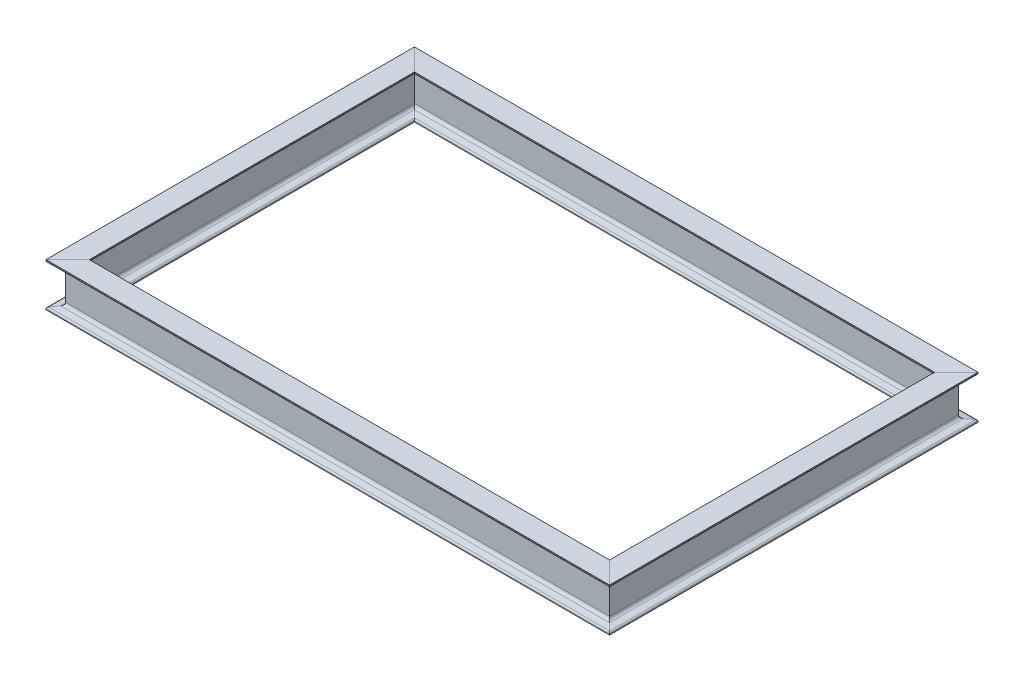
SolidWorks part; units mm, degrees
other "SB BEAM 100 x 8 x 1250 (B)"
other "SB BEAM 100 x 8 x 800 (B)"
other "SB BEAM 100 x 8 x 1250 (A)"
other "SB BEAM 100 x 8 x 800 (A)"
ref_plane "Front" through (0, 0, 0) normal (0, 0, 1) x (1, 0, 0)
ref_plane "Top" through (0, 0, 0) normal (0, 1, 0) x (1, 0, 0)
ref_plane "Right" through (0, 0, 0) normal (1, 0, 0) x (0, 0, -1)
sketch "Sketch1" plane through (0, 0, 0) normal (0, 1, 0) x (1, 0, 0)
  line L1 (-625, 400) -> (625, 400)
  line L2 (-625, 400) -> (-625, -400)
  line L3 (-625, -400) -> (625, -400)
  line L4 (625, 400) -> (625, -400)
  point P4 (0, 400)
  point P6 (-625, 0)
  dimension "D1" = 800
  dimension "D2" = 1250
other "Sb beam 100 X 8(1)"
ref_plane "Plane1" through (-625, 0, -400) normal (0, 0, 1) x (1, 0, 0)
sketch "Sketch11" plane through (-625, 0, -400) normal (0, 0, 1) x (1, 0, 0)
  line L0 (-25, -50) -> (-25, -48.0607)
  line L1 (-22.0754, -44.6083) -> (-8.0991, -42.2787)
  line L2 (-2.25, -35.374) -> (-2.25, 35.374)
  line L3 (-8.0991, 42.2787) -> (-22.0754, 44.6083)
  line L4 (-25, 48.0607) -> (-25, 50)
  line L5 (-25, 50) -> (25, 50)
  line L6 (25, 50) -> (25, 48.0607)
  line L7 (22.0754, 44.6083) -> (8.0991, 42.2787)
  line L8 (2.25, 35.374) -> (2.25, -35.374)
  line L9 (8.0991, -42.2787) -> (22.0754, -44.6083)
  line L10 (25, -48.0607) -> (25, -50)
  line L11 (25, -50) -> (-25, -50)
  line L15 (-2.25, 0) -> (2.25, 0) construction
  arc A0 (-8.0991, -42.2787) -> (-2.25, -35.374) centre (-9.25, -35.374) ccw
  arc A1 (-2.25, 35.374) -> (-8.0991, 42.2787) centre (-9.25, 35.374) ccw
  arc A2 (8.0991, 42.2787) -> (2.25, 35.374) centre (9.25, 35.374) ccw
  arc A3 (2.25, -35.374) -> (8.0991, -42.2787) centre (9.25, -35.374) ccw
  arc A4 (-22.0754, 44.6083) -> (-25, 48.0607) centre (-21.5, 48.0607) cw
  arc A5 (22.0754, 44.6083) -> (25, 48.0607) centre (21.5, 48.0607) ccw
  arc A6 (-25, -48.0607) -> (-22.0754, -44.6083) centre (-21.5, -48.0607) cw
  arc A7 (25, -48.0607) -> (22.0754, -44.6083) centre (21.5, -48.0607) ccw
  point P1 (0, 50)
  point P8 (0, -50)
  point P21 (0, 0)
  point P34 (0, 0)
  dimension "RI" = 7
  dimension "D3" = 3.5
  dimension "BF" = 50
  dimension "D2" = 9.463
  dimension "DEPTH" = 100
  dimension "TW" = 4.5
  dimension "D1" = 70.748
